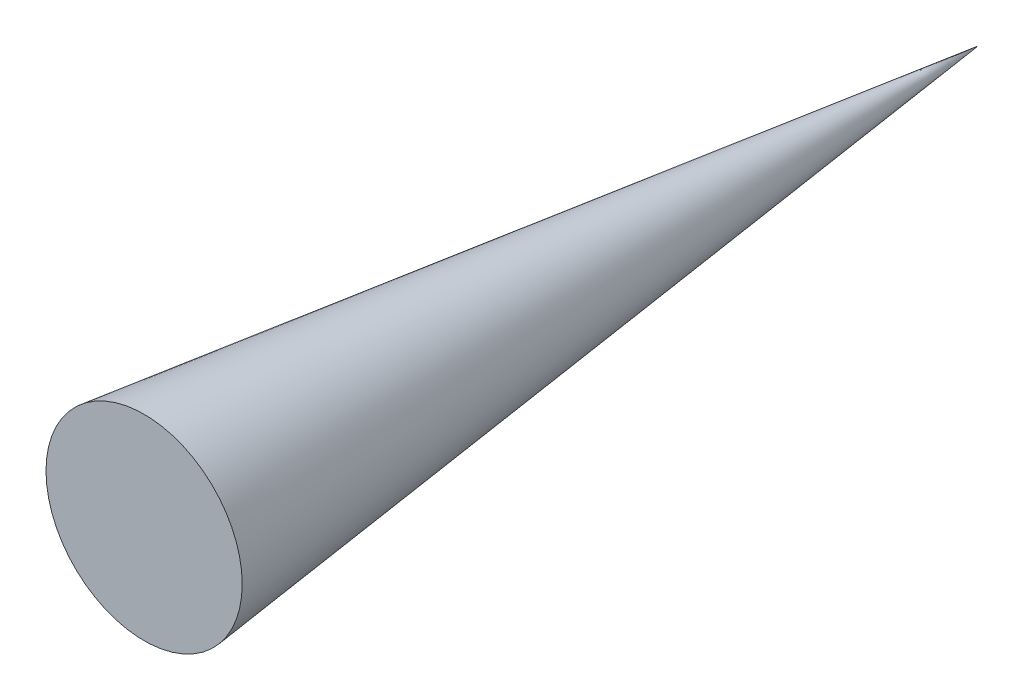
SolidWorks part; units mm, degrees
ref_plane "Front Plane" through (0, 0, 0) normal (0, 0, 1) x (1, 0, 0)
ref_plane "Top Plane" through (0, 0, 0) normal (0, 1, 0) x (1, 0, 0)
ref_plane "Right Plane" through (0, 0, 0) normal (1, 0, 0) x (0, 0, -1)
sketch "Sketch3" plane through (0, 0, 0) normal (0, 1, 0) x (1, 0, 0)
  line L0 (-14.1669, 24.4107) -> (-14.1669, -3.5232) construction
  line L1 (-14.1669, 20.2169) -> (-14.1669, 3.2169)
  line L2 (-14.1669, 3.2169) -> (-16.1669, 3.2169)
  line L3 (-14.1669, 20.2169) -> (-16.1669, 3.2169)
  dimension "D1" = 17
  dimension "D2" = 2
revolve "Revolve1" add sketch "Sketch3" angle 360 about L0
